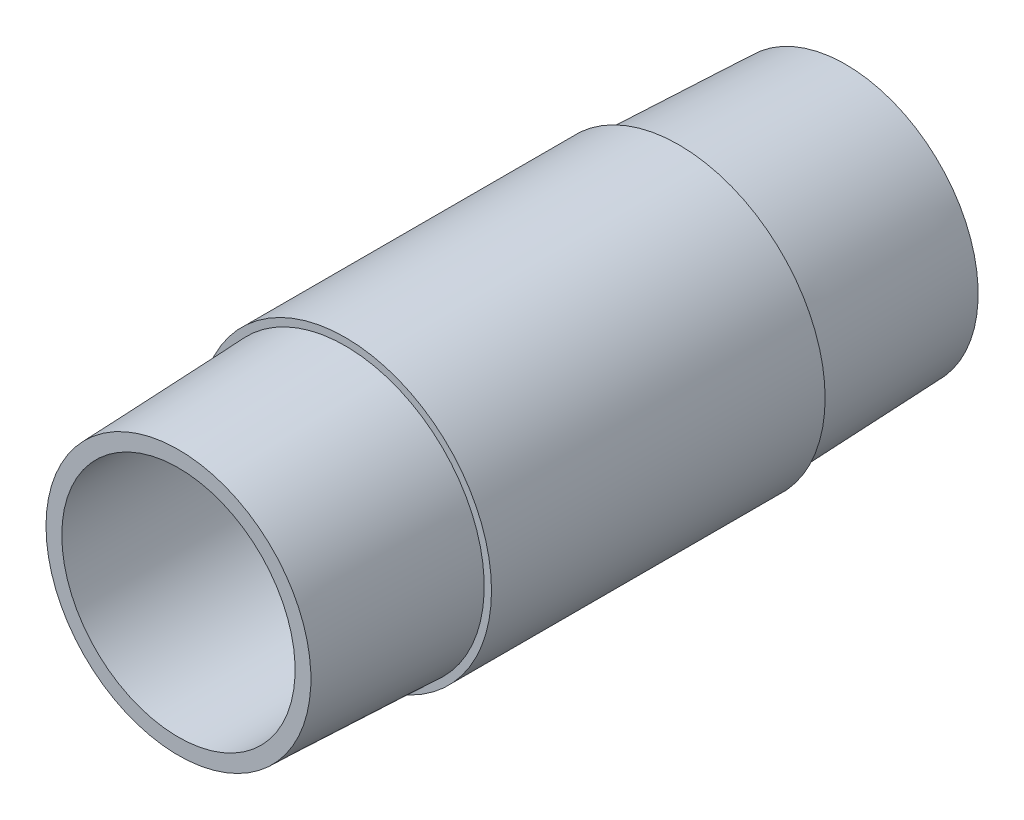
SolidWorks part; units mm, degrees
material "Plain Carbon Steel"
ref_plane "Front Plane" through (0, 0, 0) normal (0, 0, 1) x (1, 0, 0)
ref_plane "Top Plane" through (0, 0, 0) normal (0, 1, 0) x (1, 0, 0)
ref_plane "Right Plane" through (0, 0, 0) normal (1, 0, 0) x (0, 0, -1)
sketch "Sketch2" plane through (0, 0, 0) normal (0, 0, 1) x (1, 0, 0)
  circle A0 centre (0, 0) radius 13.3223
  circle A1 centre (0, 0) radius 16.7005
  dimension "D1" = 26.6446
  dimension "D2" = 33.401
extrude "Boss-Extrude1" add sketch "Sketch2" along normal blind 76.2
sketch "Sketch3" plane through (0, 0, 0) normal (1, 0, 0) x (0, 0, -1)
  line L0 (0, 21.8136) -> (-19.05, 21.8136)
  line L1 (-19.05, 21.8136) -> (-19.05, 16.7005)
  line L2 (0, 16.7005) -> (-76.2, 16.7005) construction
  line L3 (-19.05, 16.7005) -> (-19.05, 15.8693)
  line L4 (-19.05, 15.8693) -> (0, 15.1262)
  line L5 (0, -16.7005) -> (0, 16.7005) construction
  line L6 (0, 15.1262) -> (0, 21.8136)
  line L7 (-38.1, 16.7005) -> (-38.1, -16.7005) construction
  line L8 (-76.2, -16.7005) -> (0, -16.7005) construction
  line L9 (-76.2, 15.1262) -> (-76.2, 21.8136)
  line L10 (-57.15, 15.8693) -> (-76.2, 15.1262)
  line L11 (-57.15, 16.7005) -> (-57.15, 15.8693)
  line L12 (-57.15, 21.8136) -> (-57.15, 16.7005)
  line L13 (-76.2, 21.8136) -> (-57.15, 21.8136)
  line L14 (-38.1, 0) -> (-182.2331, 0) construction
  dimension "D1" = 19.05
  dimension "D2" = 19.05
revolve "Cut-Revolve2" cut sketch "Sketch3" angle 360 about L14
